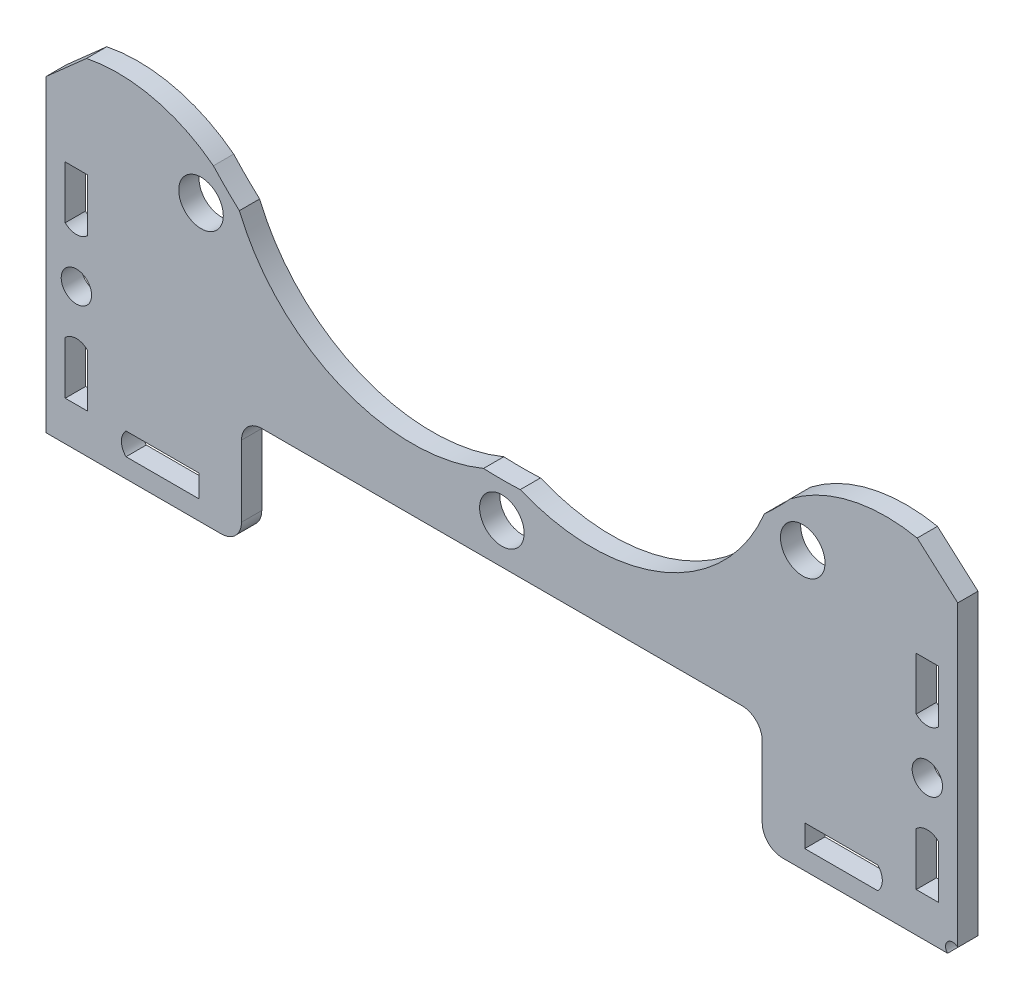
SolidWorks part; units mm, degrees
ref_plane "前视基准面" through (0, 0, 0) normal (0, 0, 1) x (1, 0, 0)
ref_plane "上视基准面" through (0, 0, 0) normal (0, 1, 0) x (1, 0, 0)
ref_plane "右视基准面" through (0, 0, 0) normal (1, 0, 0) x (0, 0, -1)
sketch "草图3" plane through (0, 0, 0) normal (0, 0, 1) x (1, 0, 0)
  line L0 (-37, -1.9902) -> (-37, -2.0902) construction
  line L2 (-41, -3.9902) -> (-42, -3.9902)
  line L4 (41, -3.9902) -> (44, -3.9902)
  line L5 (-37, 0.0098) -> (-30, 0.0098) construction
  line L6 (-37, 0.0098) -> (-37, -1.9902) construction
  line L7 (-37, -1.9902) -> (-30, -1.9902) construction
  line L8 (-30, 0.0098) -> (-30, -1.9902) construction
  line L9 (-37, -2.0902) -> (-37.1, -2.0902) construction
  line L11 (30, 0.0098) -> (37, 0.0098) construction
  line L12 (30, 0.0098) -> (30, -1.9902) construction
  line L13 (30, -1.9902) -> (37, -1.9902) construction
  line L14 (37, 0.0098) -> (37, -1.9902) construction
  line L19 (-37.1, -2.0902) -> (-29.9, -2.0902)
  line L21 (-37.1, 0.1098) -> (-29.9, 0.1098)
  line L22 (-29.9, -2.0902) -> (-29.9, 0.1098)
  line L23 (29.9, -2.0902) -> (29.9, 0.1098)
  line L24 (37.1, -2.0902) -> (29.9, -2.0902)
  line L26 (37.1, 0.1098) -> (29.9, 0.1098)
  line L39 (-41, 0.0098) -> (-44, 0.0098) construction
  line L40 (-44, 0.0098) -> (-44, 5.0098) construction
  line L41 (-44, 5.0098) -> (-41, 5.0098) construction
  line L55 (-41, 15.0098) -> (-44, 15.0098) construction
  line L56 (-44, 15.0098) -> (-44, 20.0098) construction
  line L57 (-44, 20.0098) -> (-41, 20.0098) construction
  line L79 (-41, -3.9902) -> (-27.7, -3.9902)
  line L82 (0, 10.5098) -> (0, 5.0098) construction
  line L88 (41, -3.9902) -> (27.7, -3.9902)
  line L97 (-42, 0.0098) -> (-42, 5.0098) construction
  line L98 (-42, 15.0098) -> (-42, 20.0098) construction
  line L100 (-43.1, 5.1098) -> (-43.1, -0.0902)
  line L101 (-43.1, -0.0902) -> (-40.9, -0.0902)
  line L102 (-40.9, 5.1098) -> (-40.9, -0.0902)
  line L103 (-43.1, 5.1098) -> (-40.9, -0.0902) construction
  line L104 (-43.1, -0.0902) -> (-40.9, 5.1098) construction
  line L106 (-43.1, 20.1098) -> (-40.9, 20.1098)
  line L107 (-43.1, 20.1098) -> (-43.1, 14.9098)
  line L109 (-40.9, 20.1098) -> (-40.9, 14.9098)
  line L110 (-43.1, 20.1098) -> (-40.9, 14.9098) construction
  line L111 (-43.1, 14.9098) -> (-40.9, 20.1098) construction
  line L114 (43.1, 14.9098) -> (40.9, 20.1098) construction
  line L115 (43.1, 20.1098) -> (40.9, 14.9098) construction
  line L116 (43.1, -0.0902) -> (40.9, 5.1098) construction
  line L117 (43.1, 5.1098) -> (40.9, -0.0902) construction
  line L118 (42, 15.0098) -> (42, 20.0098) construction
  line L119 (42, 0.0098) -> (42, 5.0098) construction
  line L120 (44, 20.0098) -> (41, 20.0098) construction
  line L121 (44, 15.0098) -> (44, 20.0098) construction
  line L122 (41, 15.0098) -> (44, 15.0098) construction
  line L123 (44, 5.0098) -> (41, 5.0098) construction
  line L124 (44, 0.0098) -> (44, 5.0098) construction
  line L125 (41, 0.0098) -> (44, 0.0098) construction
  line L126 (40.9, 20.1098) -> (40.9, 14.9098)
  line L128 (43.1, 20.1098) -> (43.1, 14.9098)
  line L129 (43.1, 20.1098) -> (40.9, 20.1098)
  line L130 (40.9, 5.1098) -> (40.9, -0.0902)
  line L131 (43.1, -0.0902) -> (40.9, -0.0902)
  line L132 (43.1, 5.1098) -> (43.1, -0.0902)
  line L134 (-42, -3.9902) -> (-44, -3.9902)
  line L135 (-44, -3.9902) -> (-45, -3.9902)
  line L137 (41, 30.0098) -> (45, 26.4631)
  line L139 (-40.9, 14.9098) -> (-12.7, 4.1098) construction
  line L141 (45, 15.0098) -> (45, 5.0098)
  line L142 (42, 15.0098) -> (42, 5.0098) construction
  line L143 (-44, 5.0098) -> (-44, 15.0098) construction
  line L144 (-44, 10.0098) -> (-49.7747, 10.0098) construction
  line L145 (-45, -3.9902) -> (-45, 5.0098)
  line L147 (45, 26.4631) -> (45, 15.0098)
  line L148 (45, 5.0098) -> (45, -2.9902)
  line L151 (-45, 26.4631) -> (-45, 15.0098)
  line L152 (-41, 30.0098) -> (-45, 26.4631)
  line L154 (-45, 15.0098) -> (-45, 5.0098)
  line L156 (-25.7, -3.9902) -> (25.7, -3.9902) construction
  line L157 (-25.7, -1.9902) -> (-25.7, 5.0247)
  line L158 (-23.7, 7.0247) -> (23.7, 7.0247)
  line L159 (25.7, -1.9902) -> (25.7, 5.0247)
  arc A13 (27.7, -3.9902) -> (25.7, -1.9902) centre (27.7, -1.9902) cw
  arc A14 (25.7, 5.0247) -> (23.7, 7.0247) centre (23.7, 5.0247) ccw
  arc A15 (-23.7, 7.0247) -> (-25.7, 5.0247) centre (-23.7, 5.0247) ccw
  arc A16 (-27.7, -3.9902) -> (-25.7, -1.9902) centre (-27.7, -1.9902) ccw
  arc A19 (37.1, 0.1098) -> (37.1, -2.0902) centre (36, -0.9902) cw
  arc A20 (-37.1, -2.0902) -> (-37.1, 0.1098) centre (-36, -0.9902) cw
  arc A21 (-43.1, 5.1098) -> (-40.9, 5.1098) centre (-42, 4.0098) cw
  arc A22 (-43.1, 14.9098) -> (-40.9, 14.9098) centre (-42, 16.0098) ccw
  arc A23 (40.9, 14.9098) -> (43.1, 14.9098) centre (42, 16.0098) ccw
  arc A24 (40.9, 5.1098) -> (43.1, 5.1098) centre (42, 4.0098) cw
  circle A35 centre (42, 10.0098) radius 1.5
  arc A37 (-25.9138, 24.5366) -> (-1.8118, 14.5524) centre (-8.8707, 31.5955) ccw
  arc A40 (25.9138, 24.5366) -> (1.8118, 14.5524) centre (8.8707, 31.5955) cw
  circle A41 centre (0, 53.0098) radius 38.5 construction
  arc A42 (-1.8118, 14.5524) -> (1.8118, 14.5524) centre (0, 53.0098) ccw
  circle A43 centre (-42, 10.0098) radius 1.5
  circle A46 centre (0, 53.0098) radius 42 construction
  arc A47 (-25.9138, 24.5366) -> (-28.4742, 27.0971) centre (0, 53.0098) cw
  arc A48 (-41, 30.0098) -> (-28.4742, 27.0971) centre (-37.9195, 14.8681) cw
  arc A49 (25.9138, 24.5366) -> (28.4742, 27.0971) centre (0, 53.0098) ccw
  arc A50 (41, 30.0098) -> (28.4742, 27.0971) centre (37.9195, 14.8681) ccw
  circle A51 centre (0, 11.0098) radius 2.2
  circle A52 centre (-29.6985, 23.3113) radius 2.2
  circle A58 centre (29.6985, 23.3113) radius 2.2
  arc A64 (44, -3.9902) -> (45, -2.9902) centre (44.5, -3.4902) cw
  point P39 (-42, 2.5098)
  point P55 (-42, 17.5098)
  point P90 (42, 17.5098)
  point P91 (42, 2.5098)
  dimension "D2" = 2
extrude "凸台-拉伸1" add sketch "草图3" along normal blind 2
